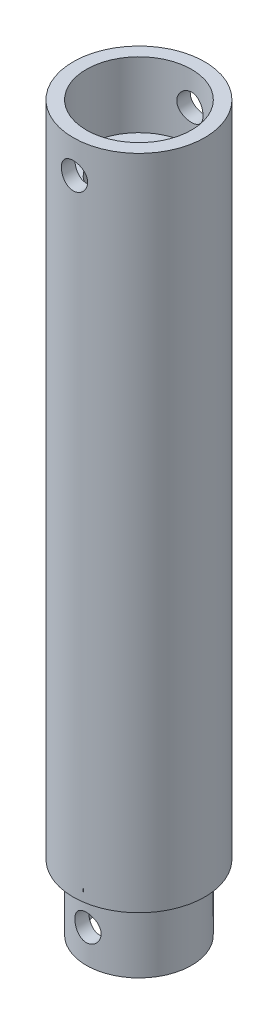
SolidWorks part; units mm, degrees
ref_plane "Front Plane" through (0, 0, 0) normal (0, 0, 1) x (1, 0, 0)
ref_plane "Top Plane" through (0, 0, 0) normal (0, 1, 0) x (1, 0, 0)
ref_plane "Right Plane" through (0, 0, 0) normal (1, 0, 0) x (0, 0, -1)
sketch "Sketch2" plane through (0, 0, 0) normal (0, 1, 0) x (1, 0, 0)
  circle A0 centre (0, 0) radius 7.9
extrude "Boss-Extrude1" add sketch "Sketch2" along normal blind 5
sketch "Sketch3" plane through (0, 5, 0) normal (0, 1, 0) x (1, 0, 0)
  circle A0 centre (0, 0) radius 10
extrude "Boss-Extrude2" add sketch "Sketch3" along normal blind 100
sketch "Sketch4" plane through (0, 105, 0) normal (0, 1, 0) x (1, 0, 0)
  circle A0 centre (0, 0) radius 6
extrude "Cut-Extrude2" cut sketch "Sketch4" against normal blind 200
sketch "Sketch5" plane through (0, 0, 0) normal (0, -1, 0) x (-1, 0, 0)
  circle A0 centre (0, 0) radius 8
extrude "Boss-Extrude3" add sketch "Sketch5" against normal blind 5 contours A0
sketch "Sketch6" plane through (0, 0, 0) normal (0, -1, 0) x (-1, 0, 0)
  circle A0 centre (0, 0) radius 6
extrude "Cut-Extrude3" cut sketch "Sketch6" against normal blind 5
ref_plane "Plane1" through (0, 0, 10) normal (0, 0, 1) x (1, 0, 0)
sketch "Sketch10" plane through (0, 0, 0) normal (0, -1, 0) x (-1, 0, 0)
  circle A0 centre (0, 0) radius 8
extrude "Boss-Extrude5" add sketch "Sketch10" along normal blind 5
sketch "Sketch11" plane through (0, -5, 0) normal (0, -1, 0) x (-1, 0, 0)
  circle A0 centre (0, 0) radius 6
extrude "Cut-Extrude5" cut sketch "Sketch11" against normal blind 10
sketch "Sketch12" plane through (0, 0, 10) normal (0, 0, 1) x (1, 0, 0)
  circle A0 centre (0, 0) radius 2
extrude "Cut-Extrude6" cut sketch "Sketch12" against normal blind 20
sketch "Sketch13" plane through (0, 0, 10) normal (0, 0, 1) x (1, 0, 0)
  line L0 (0, 105) -> (0, 100)
  line L1 (6, 105) -> (-6, 105) construction
  circle A0 centre (0, 100) radius 2
extrude "Cut-Extrude7" cut sketch "Sketch13" against normal blind 20
sketch "Sketch15" plane through (0, 105, 0) normal (0, 1, 0) x (1, 0, 0)
  circle A0 centre (0, 0) radius 8
extrude "Cut-Extrude9" cut sketch "Sketch15" against normal blind 10
